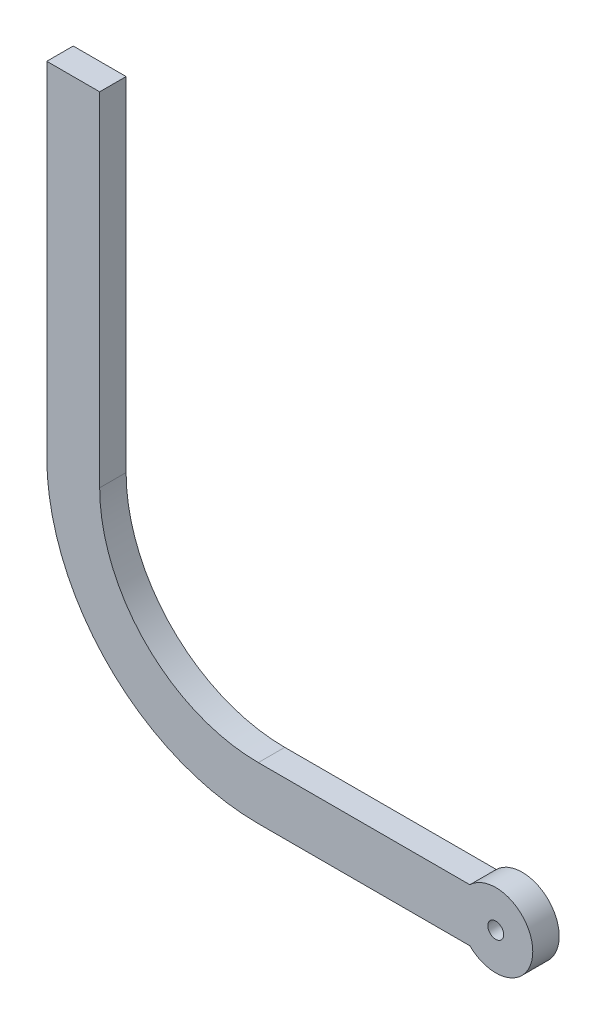
SolidWorks part; units mm, degrees
ref_plane "Front Plane" through (0, 0, 0) normal (0, 0, 1) x (1, 0, 0)
ref_plane "Top Plane" through (0, 0, 0) normal (0, 1, 0) x (1, 0, 0)
ref_plane "Right Plane" through (0, 0, 0) normal (1, 0, 0) x (0, 0, -1)
sketch "Sketch1" plane through (0, 0, 0) normal (0, 0, 1) x (1, 0, 0)
  line L2 (0, 0) -> (-41.8502, 0) construction
  line L14 (-4.899, 5) -> (-44.899, 5)
  line L17 (-74.899, 35) -> (-74.899, 99.8542)
  line L18 (-74.899, 99.8542) -> (-84.899, 99.8542)
  line L19 (-84.899, 99.8542) -> (-84.899, 35)
  line L21 (-44.899, -5) -> (-4.899, -5)
  arc A0 (-4.899, -5) -> (-4.899, 5) centre (0, 0) ccw
  circle A1 centre (0, 0) radius 1.5
  arc A12 (-74.899, 35) -> (-44.899, 5) centre (-44.899, 35) ccw
  arc A13 (-84.899, 35) -> (-44.899, -5) centre (-44.899, 35) ccw
  dimension "D1" = 14
  dimension "D6" = 3
  dimension "D3" = 80
  dimension "D2" = 60
  dimension "D4" = 10
extrude "Boss-Extrude1" add sketch "Sketch1" along normal blind 5
